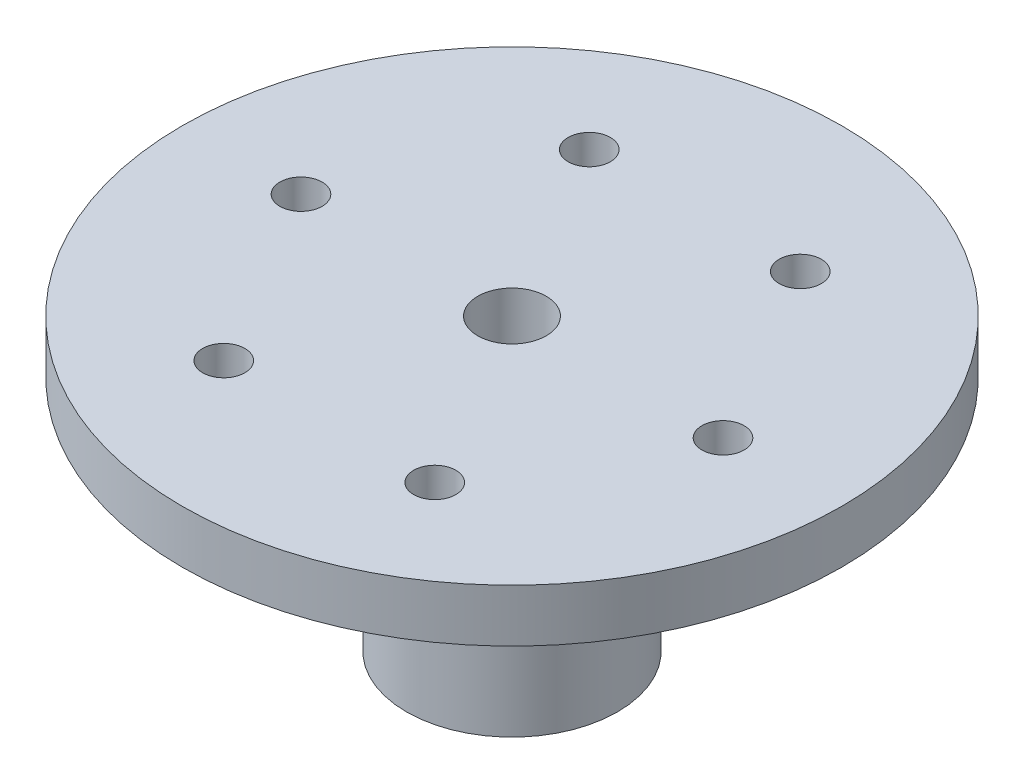
SolidWorks part; units mm, degrees
ref_plane "前视基准面" through (0, 0, 0) normal (0, 0, 1) x (1, 0, 0)
ref_plane "上视基准面" through (0, 0, 0) normal (0, 1, 0) x (1, 0, 0)
ref_plane "右视基准面" through (0, 0, 0) normal (1, 0, 0) x (0, 0, -1)
sketch "草图1" plane through (0, 0, 0) normal (0, 1, 0) x (1, 0, 0)
  circle A0 centre (0, 0) radius 2.6
  circle A1 centre (0, 0) radius 8
  dimension "D1" = 5.2
  dimension "D2" = 16
extrude "凸台-拉伸1" add sketch "草图1" along normal blind 18
sketch "草图2" plane through (0, 18, 0) normal (0, 1, 0) x (1, 0, 0)
  line L0 (0, 0) -> (50000, 0) construction
  circle A0 centre (0, 0) radius 25
  circle A1 centre (16, 0) radius 1.6
  circle A2 centre (8, -13.8564) radius 1.6
  circle A3 centre (-8, -13.8564) radius 1.6
  circle A4 centre (-16, 0) radius 1.6
  circle A5 centre (-8, 13.8564) radius 1.6
  circle A6 centre (8, 13.8564) radius 1.6
  point P19 (0, 0)
  dimension "D1" = 50
  dimension "D2" = 3.2
  dimension "D3" = 16
  dimension "D4" = 6
extrude "凸台-拉伸2" add sketch "草图2" along normal blind 4
sketch "草图4" plane through (0, 0, 0) normal (0, 0, 1) x (1, 0, 0)
  line L0 (-8, 0) -> (8, 0) construction
  circle A0 centre (0, 10) radius 2.4
  dimension "D1" = 4.8
  dimension "D2" = 10
extrude "切除-拉伸1" cut sketch "草图4" against normal blind 10 contours A0
sketch "草图5" plane through (0, 18, 0) normal (0, -1, 0) x (1, 0, 0)
  circle A0 centre (0, 0) radius 2.6
extrude "切除-拉伸2" cut sketch "草图5" against normal blind 10
